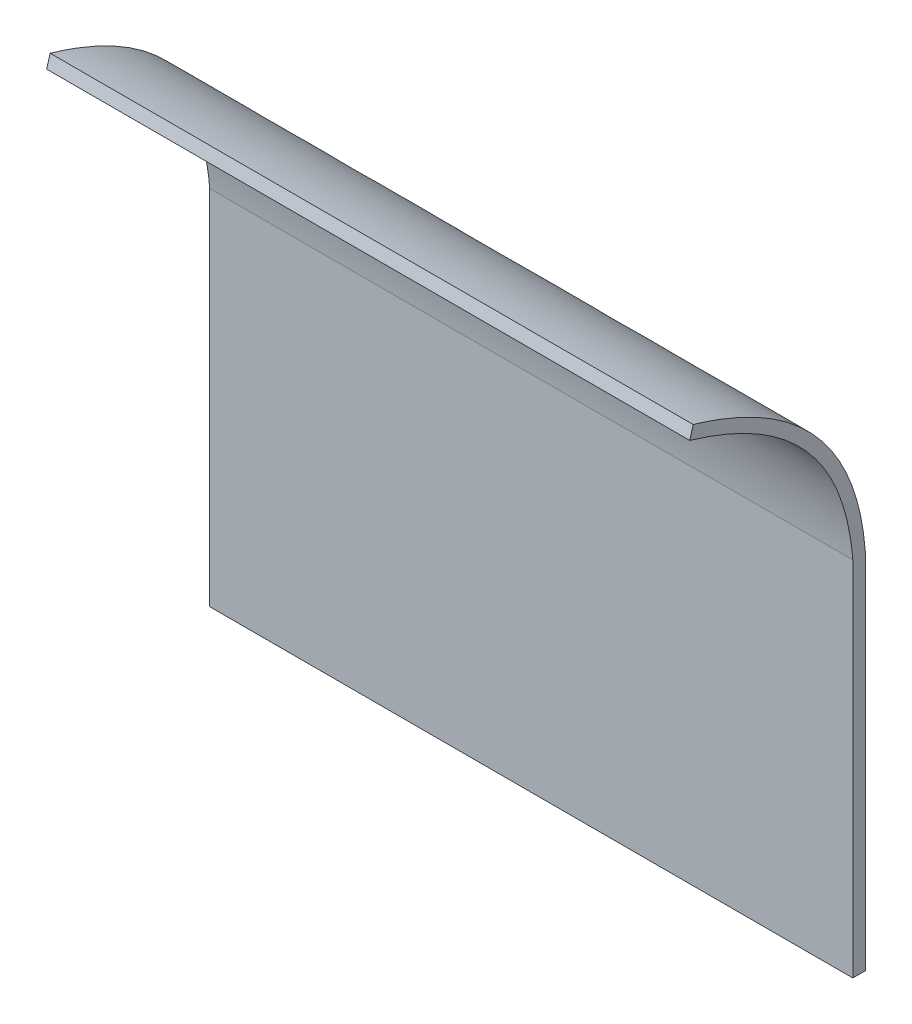
SolidWorks part; units mm, degrees
ref_plane "Plan de face" through (0, 0, 0) normal (0, 0, 1) x (1, 0, 0)
ref_plane "Plan de dessus" through (0, 0, 0) normal (0, 1, 0) x (1, 0, 0)
ref_plane "Plan de droite" through (0, 0, 0) normal (1, 0, 0) x (0, 0, -1)
sketch "Esquisse2" plane through (0, 0, 0) normal (1, 0, 0) x (0, 0, -1)
  line L0 (20.1758, 57.7966) -> (20.1758, 0)
  line L1 (18.1758, 57.7198) -> (18.1758, 0)
  line L2 (-7.2595, 89.1187) -> (-7.816, 87.1977)
  line L3 (20.1758, 0) -> (18.1758, 0)
  spline S0 degree 1 poles (18.1758, 57.7198) (-7.816, 87.1977) knots 0 0 1 1 construction
  spline S1 degree 2 poles (20.1758, 57.7966) (18.36, 81.6963) (-7.2595, 89.1187) knots 0.581249 0.581249 0.581249 1 1 1
  spline S2 degree 2 poles (-7.816, 87.1977) (1.4582, 84.4867) (11.2356, 76.5134) (17.4937, 66.2372) (18.1758, 57.7198) knots 0.581934 0.581934 0.581934 0.738709 0.843225 1 1 1
  dimension "D1" = 2
extrude "Boss.-Extru.1" add sketch "Esquisse2" along normal blind 102.5
sketch "Esquisse3" plane through (0, 0, 0) normal (0, -1, 0) x (1, 0, 0)
  line L0 (0, -20.1758) -> (12, -20.1758)
  line L1 (0, -20.1758) -> (0, -12.1758)
  line L2 (12, -20.1758) -> (12, -12.1758)
  line L3 (0, -12.1758) -> (12, -12.1758)
  line L4 (102.5, -20.1758) -> (0, -20.1758) construction
  line L5 (51.25, -20.1758) -> (51.25, 7.816) construction
  line L6 (102.5, 7.816) -> (0, 7.816) construction
  arc A0 (0, -12.1758) -> (12, -12.1758) centre (6, -12.1758) cw
  circle A1 centre (6, -12.1758) radius 1.75
  dimension "D1" = 6
  dimension "D3" = 3.5
  dimension "D2" = 8
